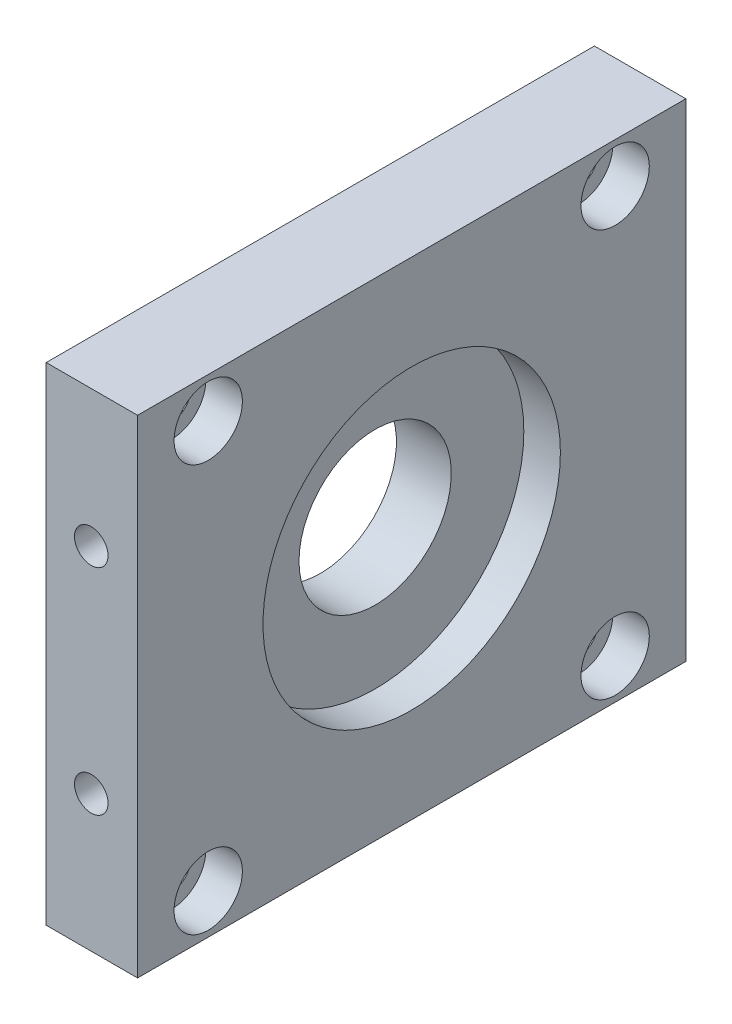
SolidWorks part; units mm, degrees
ref_plane "Front Plane" through (0, 0, 0) normal (1, 0, 0) x (0, 1, 0)
ref_plane "Top Plane" through (0, 0, 0) normal (0, 0, 1) x (0, 1, 0)
ref_plane "Right Plane" through (0, 0, 0) normal (0, 1, 0) x (-1, 0, 0)
sketch "Sketch1" plane through (0, 0, 0) normal (1, 0, 0) x (0, 1, 0)
  line L1 (0, 0) -> (101.6, 0)
  line L2 (0, 0) -> (0, 114.3)
  line L3 (0, 114.3) -> (101.6, 114.3)
  line L4 (101.6, 0) -> (101.6, 114.3)
  dimension "D1" = 114.3
  dimension "D2" = 101.6
extrude "Boss-Extrude1" add sketch "Sketch1" along normal blind 19.05
sketch "Sketch2" plane through (19.05, 0, 0) normal (1, 0, 0) x (0, 1, 0)
  line L0 (0, 114.3) -> (50.8, 114.3) construction
  line L1 (101.6, 114.3) -> (0, 114.3) construction
  line L2 (50.8, 114.3) -> (50.8, 0) construction
  line L3 (0, 0) -> (101.6, 0) construction
  circle A0 centre (50.8, 57.15) radius 30.9999
  dimension "D1" = 61.9999
extrude "Cut-Extrude1" cut sketch "Sketch2" against normal blind 7.62
sketch "Sketch4" plane through (0, 0, 0) normal (-1, 0, 0) x (0, -1, 0)
  line L0 (-101.6, 114.3) -> (-50.8, 114.3) construction
  line L1 (-101.6, 114.3) -> (0, 114.3) construction
  line L2 (-50.8, 114.3) -> (-50.8, 0) construction
  line L3 (0, 0) -> (-101.6, 0) construction
  circle A0 centre (-50.8, 57.15) radius 15.875
  dimension "D1" = 31.75
extrude "Cut-Extrude2" cut sketch "Sketch4" against normal through all
sketch "Sketch5" plane through (19.05, 0, 0) normal (1, 0, 0) x (0, 1, 0)
  line L0 (0, 99.568) -> (0, 14.732) construction
  line L1 (0, 114.3) -> (0, 0) construction
  line L2 (101.6, 99.568) -> (101.6, 14.732) construction
  line L3 (101.6, 0) -> (101.6, 114.3) construction
  line L4 (0, 99.568) -> (8.382, 99.568) construction
  line L5 (101.6, 99.568) -> (93.218, 99.568) construction
  line L6 (101.6, 14.732) -> (93.218, 14.732) construction
  line L7 (0, 14.732) -> (8.382, 14.732) construction
  line L8 (8.382, 0) -> (93.218, 0) construction
  line L9 (0, 0) -> (101.6, 0) construction
  line L11 (93.218, 0) -> (93.218, 14.732) construction
  line L13 (8.382, 0) -> (8.382, 14.732) construction
  circle A0 centre (8.382, 99.568) radius 4.0005
  circle A1 centre (93.218, 99.568) radius 4.0005
  circle A2 centre (93.218, 14.732) radius 4.0005
  circle A3 centre (8.382, 14.732) radius 4.0005
  point P5 (0, 57.15)
  point P10 (101.6, 57.15)
  point P11 (8.382, 99.568)
  point P12 (93.218, 99.568)
  point P13 (93.218, 14.732)
  point P14 (8.382, 14.732)
  point P25 (0, 57.15)
  point P75 (50.8, 0)
  dimension "D7" = 8.001
  dimension "D8" = 8.001
  dimension "D9" = 8.001
  dimension "D10" = 8.001
  dimension "D1" = 84.836
  dimension "D2" = 84.836
  dimension "D3" = 8.382
  dimension "D4" = 8.382
  dimension "D5" = 8.382
  dimension "D6" = 8.382
  dimension "D11" = 84.836
extrude "Cut-Extrude4" cut sketch "Sketch5" against normal through all contours A0 | A2 | A1 | A3
sketch "Sketch10" plane through (19.05, 0, 0) normal (1, 0, 0) x (0, 1, 0)
  circle A0 centre (8.382, 99.568) radius 7.125
  circle A1 centre (93.218, 99.568) radius 7.125
  circle A2 centre (93.218, 14.732) radius 7.125
  circle A3 centre (8.382, 14.732) radius 7.125
  dimension "D1" = 14.25
  dimension "D2" = 14.25
  dimension "D3" = 14.25
  dimension "D4" = 14.25
extrude "Cut-Extrude5" cut sketch "Sketch10" against normal blind 7.62
sketch "Sketch15" plane through (0, 0, 114.3) normal (0, 0, 1) x (1, 0, 0)
  line L0 (0, 0) -> (0, 28.448) construction
  line L1 (0, 101.6) -> (0, 0) construction
  line L2 (0, 28.448) -> (9.398, 28.448) construction
  line L3 (0, 101.6) -> (0, 73.152) construction
  line L4 (0, 73.152) -> (9.398, 73.152) construction
  point P6 (9.398, 28.448)
  point P10 (9.398, 73.152)
  dimension "D1" = 28.448
  dimension "D2" = 9.398
hole_wizard "Tap Drill for M8x1.0 Tap2" positions "Sketch15" profile "Sketch16" hole size "M8x1.0" standard "ANSI Metric"
sketch "Sketch16" plane through (9.398, 73.152, 114.3) normal (1, 0, 0) x (0, -1, 0)
  line L0 (0, 0) -> (0, 27.503)
  line L1 (0, 27.503) -> (3.5, 25.4)
  line L2 (3.5, 25.4) -> (3.5, 0)
  line L5 (3.5, 0) -> (0, 0)
  line L10 (0, 27.503) -> (-3.5, 25.4) construction
  line L11 (0, -6.35) -> (0, 107.95) construction
  dimension "Hole Dia." = 7
  dimension "Hole Depth" = 25.4
  dimension "Drill Angle" = 118
sketch "Sketch17" plane through (0, 0, 0) normal (0, 0, -1) x (1, 0, 0)
  line L0 (0, 0) -> (0, -28.448) construction
  line L1 (0, 0) -> (0, -101.6) construction
  line L2 (0, -28.448) -> (9.398, -28.448) construction
  line L3 (0, -101.6) -> (0, -73.152) construction
  line L4 (0, -73.152) -> (9.398, -73.152) construction
  point P6 (9.398, -28.448)
  point P10 (9.398, -73.152)
  dimension "D1" = 28.448
  dimension "D2" = 9.398
  dimension "D3" = 28.448
  dimension "D4" = 9.398
hole_wizard "Tap Drill for M8x1.0 Tap3" positions "Sketch17" profile "Sketch18" hole size "M8x1.0" standard "ANSI Metric"
sketch "Sketch18" plane through (9.398, 73.152, 0) normal (1, 0, 0) x (0, 1, 0)
  line L0 (0, 0) -> (0, 27.503)
  line L1 (0, 27.503) -> (3.5, 25.4)
  line L2 (3.5, 25.4) -> (3.5, 0)
  line L5 (3.5, 0) -> (0, 0)
  line L10 (0, 27.503) -> (-3.5, 25.4) construction
  line L11 (0, -6.35) -> (0, 107.95) construction
  dimension "Hole Dia." = 7
  dimension "Hole Depth" = 25.4
  dimension "Drill Angle" = 118
